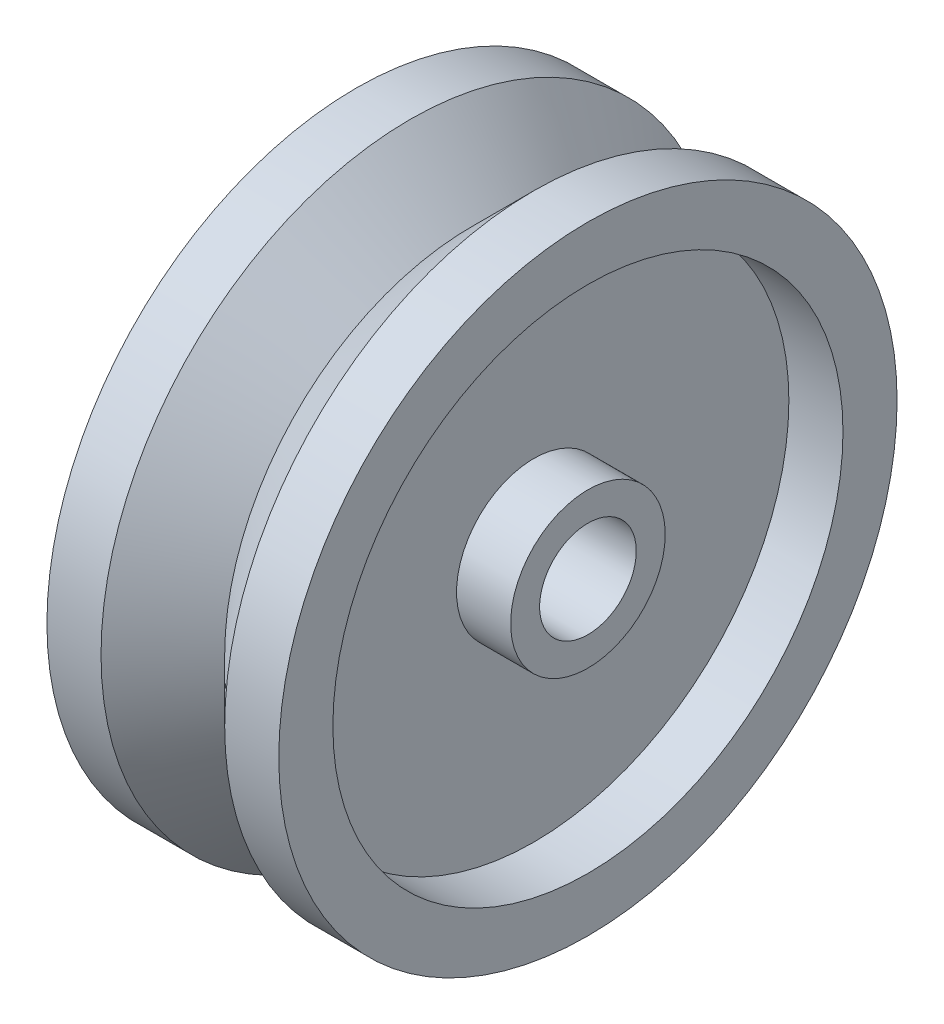
SolidWorks part; units mm, degrees
ref_plane "Front Plane" through (0, 0, 0) normal (0, 0, 1) x (1, 0, 0)
ref_plane "Top Plane" through (0, 0, 0) normal (0, 1, 0) x (1, 0, 0)
ref_plane "Right Plane" through (0, 0, 0) normal (1, 0, 0) x (0, 0, -1)
sketch "Sketch2" plane through (0, 0, 0) normal (1, 0, 0) x (0, 0, -1)
  circle A0 centre (0, 0) radius 20
  dimension "D1" = 40
extrude "Boss-Extrude1" add sketch "Sketch2" along normal blind 15
sketch "Sketch3" plane through (15, 0, 0) normal (1, 0, 0) x (0, 0, -1)
  circle A0 centre (0, 0) radius 16.5
  circle A1 centre (0, 0) radius 5
  dimension "D1" = 33
  dimension "D2" = 10
extrude "Cut-Extrude1" cut sketch "Sketch3" against normal blind 3.5
sketch "Sketch4" plane through (0, 0, 0) normal (-1, 0, 0) x (0, 0, 1)
  circle A1 centre (0, 0) radius 16.5
  circle A2 centre (0, 0) radius 16.5
  circle A3 centre (0, 0) radius 5
  circle A4 centre (0, 0) radius 5
  dimension "D1" = 0
  dimension "D2" = 0
extrude "Cut-Extrude2" cut sketch "Sketch4" against normal blind 3.5
sketch "Sketch6" plane through (15, 0, 0) normal (1, 0, 0) x (0, 0, -1)
  circle A0 centre (0, 0) radius 3.125
  dimension "D1" = 6.25
extrude "Cut-Extrude3" cut sketch "Sketch6" against normal through all
sketch "Sketch7" plane through (0, 0, 0) normal (0, 1, 0) x (1, 0, 0)
  line L0 (0, 0) -> (15, 0) construction
  line L1 (15, -20) -> (15, 20) construction
  line L2 (7.5, 0) -> (7.5, 20) construction
  line L3 (15, 20) -> (0, 20) construction
  line L4 (7.5, 0) -> (7.5, -20) construction
  line L5 (0, -20) -> (15, -20) construction
  line L6 (3.5, 20) -> (7.5, 16)
  line L7 (7.5, 16) -> (11.5, 20)
  line L8 (3.5, 20) -> (11.5, 20)
  line L9 (3.5, 20) -> (3.5, -20) construction
  line L10 (11.5, 20) -> (11.5, -20) construction
  dimension "D1" = 3.5
  dimension "D2" = 3.5
  dimension "D3" = 90
revolve "Cut-Revolve3" cut sketch "Sketch7" angle 360 about L0
